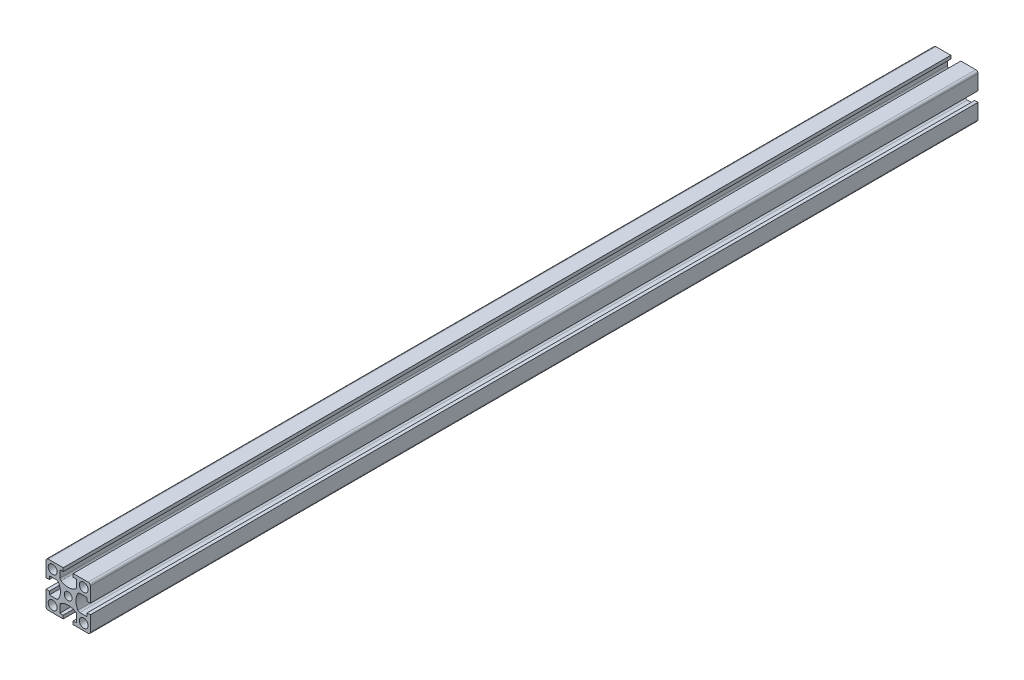
SolidWorks part; units mm, degrees
ref_plane "Front Plane" through (0, 0, 0) normal (0, 0, 1) x (1, 0, 0)
ref_plane "Top Plane" through (0, 0, 0) normal (0, 1, 0) x (1, 0, 0)
ref_plane "Right Plane" through (0, 0, 0) normal (1, 0, 0) x (0, 0, -1)
sketch "Sketch1" plane through (0, 0, 0) normal (0, 0, 1) x (1, 0, 0)
  line L64 (-20, 18) -> (-20, 4.5)
  line L65 (-20, 4.5) -> (-17, 4.5)
  line L66 (-17, 4.5) -> (-17, 7.5)
  line L67 (-17, 7.5) -> (-10.4737, 7.5)
  line L68 (-10.4737, -7.5) -> (-17, -7.5)
  line L69 (-17, -7.5) -> (-17, -4.5)
  line L70 (-17, -4.5) -> (-20, -4.5)
  line L71 (-20, -4.5) -> (-20, -18)
  line L72 (-18, -20) -> (-4.5, -20)
  line L73 (-4.5, -20) -> (-4.5, -17)
  line L74 (-4.5, -17) -> (-7.5, -17)
  line L75 (-7.5, -17) -> (-7.5, -10.4737)
  line L76 (7.5, -10.4737) -> (7.5, -17)
  line L77 (7.5, -17) -> (4.5, -17)
  line L78 (4.5, -17) -> (4.5, -20)
  line L79 (4.5, -20) -> (18, -20)
  line L80 (20, -18) -> (20, -4.5)
  line L81 (20, -4.5) -> (17, -4.5)
  line L82 (17, -4.5) -> (17, -7.5)
  line L83 (17, -7.5) -> (10.4737, -7.5)
  line L84 (10.4737, 7.5) -> (17, 7.5)
  line L85 (17, 7.5) -> (17, 4.5)
  line L86 (17, 4.5) -> (20, 4.5)
  line L87 (20, 4.5) -> (20, 18)
  line L88 (18, 20) -> (4.5, 20)
  line L89 (4.5, 20) -> (4.5, 17)
  line L90 (4.5, 17) -> (7.5, 17)
  line L91 (7.5, 17) -> (7.5, 10.4737)
  line L92 (-7.5, 10.4737) -> (-7.5, 17)
  line L93 (-7.5, 17) -> (-4.5, 17)
  line L94 (-4.5, 17) -> (-4.5, 20)
  line L95 (-4.5, 20) -> (-18, 20)
  circle A5 centre (-14, -14) radius 4
  circle A6 centre (14, -14) radius 4
  circle A7 centre (14, 14) radius 4
  circle A8 centre (0, 0) radius 3.5
  circle A9 centre (-14, 14) radius 4
  arc A32 (-18, 20) -> (-20, 18) centre (-18, 18) ccw
  arc A33 (-8.7417, 6.5) -> (-10.4737, 7.5) centre (-10.4737, 5.5) ccw
  arc A34 (-8.7417, -6.5) -> (-8.7417, 6.5) centre (-20, 0) ccw
  arc A35 (-10.4737, -7.5) -> (-8.7417, -6.5) centre (-10.4737, -5.5) ccw
  arc A36 (-20, -18) -> (-18, -20) centre (-18, -18) ccw
  arc A37 (-6.5, -8.7417) -> (-7.5, -10.4737) centre (-5.5, -10.4737) ccw
  arc A38 (6.5, -8.7417) -> (-6.5, -8.7417) centre (0, -20) ccw
  arc A39 (7.5, -10.4737) -> (6.5, -8.7417) centre (5.5, -10.4737) ccw
  arc A40 (18, -20) -> (20, -18) centre (18, -18) ccw
  arc A41 (8.7417, -6.5) -> (10.4737, -7.5) centre (10.4737, -5.5) ccw
  arc A42 (8.7417, 6.5) -> (8.7417, -6.5) centre (20, 0) ccw
  arc A43 (10.4737, 7.5) -> (8.7417, 6.5) centre (10.4737, 5.5) ccw
  arc A44 (20, 18) -> (18, 20) centre (18, 18) ccw
  arc A45 (6.5, 8.7417) -> (7.5, 10.4737) centre (5.5, 10.4737) ccw
  arc A46 (-6.5, 8.7417) -> (6.5, 8.7417) centre (0, 20) ccw
  arc A47 (-7.5, 10.4737) -> (-6.5, 8.7417) centre (-5.5, 10.4737) ccw
extrude "Boss-Extrude1" add sketch "Sketch1" along normal blind 800
